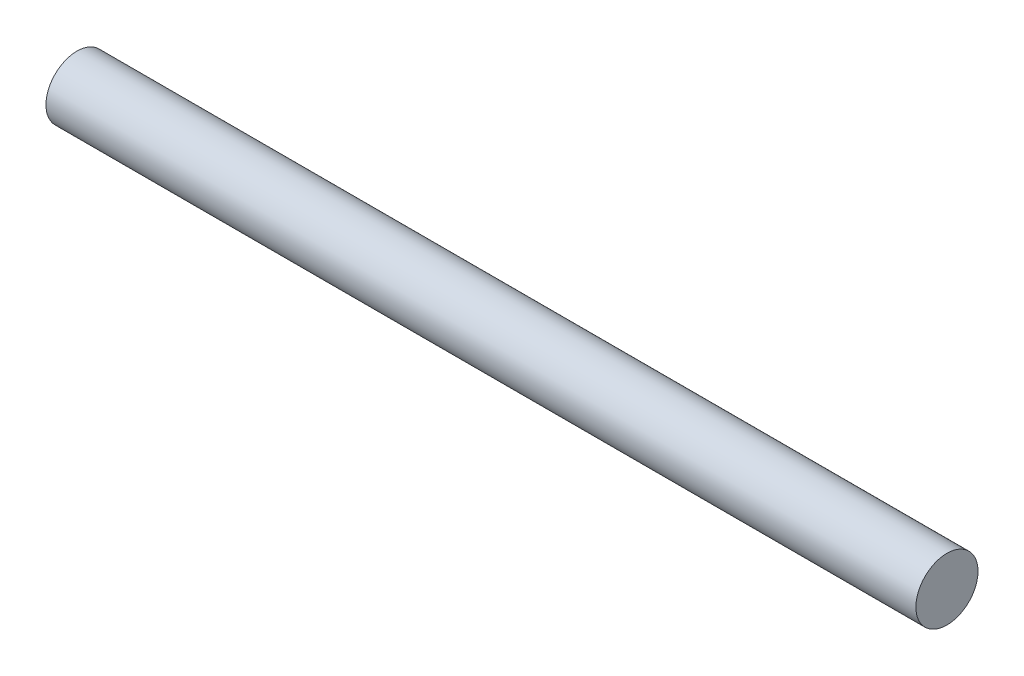
SolidWorks part; units mm, degrees
ref_plane "Front Plane" through (0, 0, 0) normal (1, 0, 0) x (0, 1, 0)
ref_plane "Top Plane" through (0, 0, 0) normal (0, 0, 1) x (0, 1, 0)
ref_plane "Right Plane" through (0, 0, 0) normal (0, 1, 0) x (-1, 0, 0)
sketch "Sketch1" plane through (0, 0, 0) normal (1, 0, 0) x (0, 1, 0)
  circle A0 centre (0, 0) radius 7.5
  dimension "D1" = 15
extrude "Boss-Extrude1" add sketch "Sketch1" along normal blind 210
